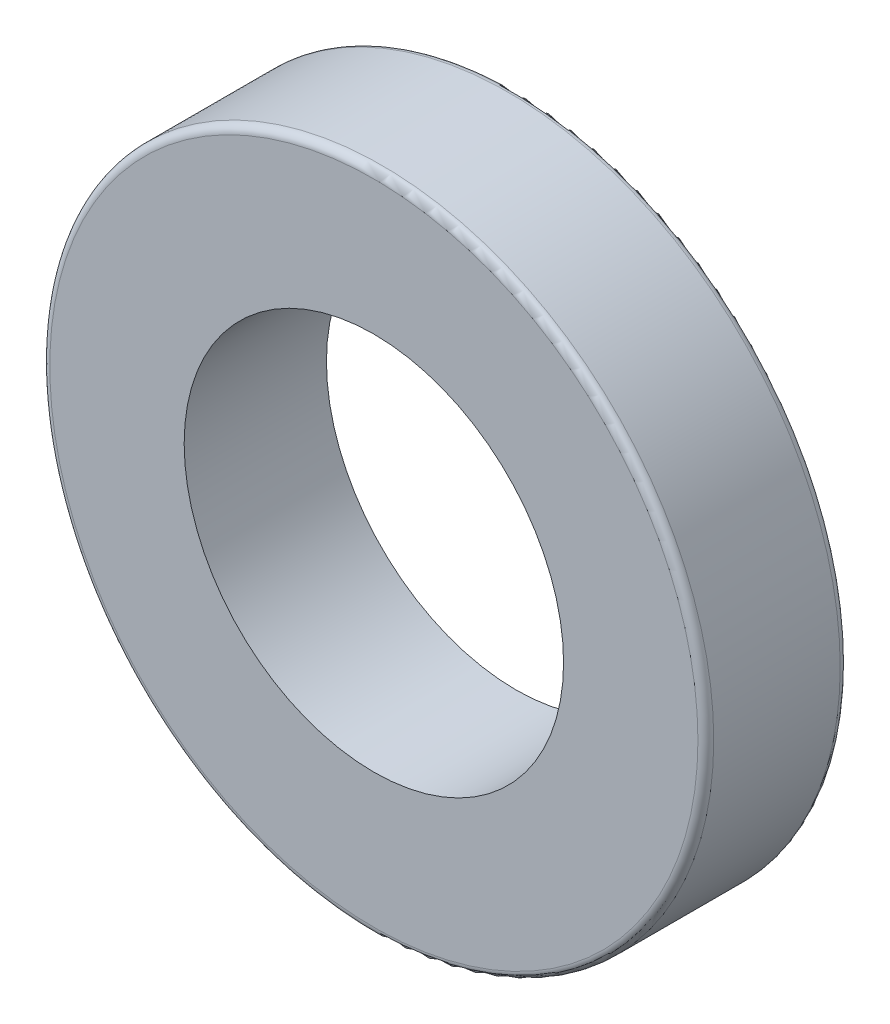
SolidWorks part; units mm, degrees
ref_plane "前视基准面" through (0, 0, 0) normal (0, 0, 1) x (1, 0, 0)
ref_plane "上视基准面" through (0, 0, 0) normal (0, 1, 0) x (1, 0, 0)
ref_plane "右视基准面" through (0, 0, 0) normal (1, 0, 0) x (0, 0, -1)
sketch "Sketch1" plane through (0, 0, 0) normal (0, 0, 1) x (1, 0, 0)
  circle A0 centre (0, 0) radius 12
  circle A1 centre (0, 0) radius 21
  dimension "D1" = 24
  dimension "D2" = 42
extrude "Boss-Extrude1" add sketch "Sketch1" against normal blind 9
fillet "Fillet1" radius 0.5 2 edges at (21, 0, 0) (21, 0, -9)
